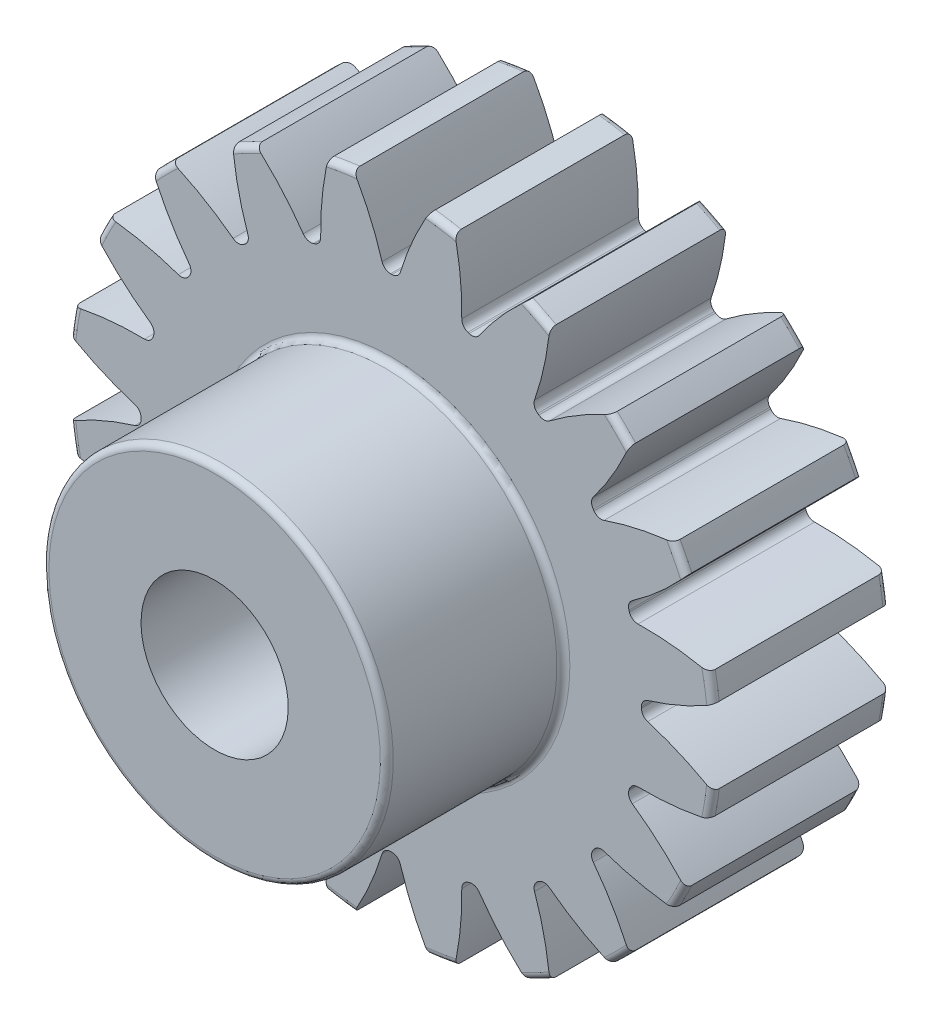
SolidWorks part; units mm, degrees
ref_plane "Front Plane" through (0, 0, 0) normal (0, 0, 1) x (1, 0, 0)
ref_plane "Top Plane" through (0, 0, 0) normal (0, 1, 0) x (1, 0, 0)
ref_plane "Right Plane" through (0, 0, 0) normal (1, 0, 0) x (0, 0, -1)
sketch "Sketch1" plane through (0, 0, 0) normal (0, 0, 1) x (1, 0, 0)
  line L0 (-254, 0) -> (254, 0) construction
  circle A0 centre (0, 0) radius 11 construction
  circle A1 centre (0, 0) radius 10 construction
  circle A2 centre (0, 0) radius 8.5 construction
  circle A3 centre (0, 0) radius 5.85 construction
  circle A4 centre (0, 0) radius 2.5 construction
  dimension "D2" = 1
  dimension "D3" = 2.5
  dimension "D1" = 2.5
sketch "Sketch2" plane through (0, 0, 0) normal (1, 0, 0) x (0, 0, -1)
  line L0 (0, 0) -> (-6, 0) construction
  line L1 (-6, 0) -> (-12, 0) construction
  dimension "Overall Width" = 12
  dimension "Face Width" = 6
sketch "Sketch4" plane through (0, 0, 0) normal (1, 0, 0) x (0, 0, -1)
  line L0 (-12, 2.5) -> (-12, 5.85)
  line L1 (-12, 5.85) -> (-6, 5.85)
  line L2 (-6, 5.85) -> (-6, 11)
  line L3 (-6, 11) -> (0, 11)
  line L4 (0, 11) -> (0, 2.5)
  line L5 (-6, 5.85) -> (-6, 0) construction
  line L6 (0, 11) -> (0, -11) construction
  line L7 (-6, 5.85) -> (0, 5.85) construction
  line L12 (-12, 2.5) -> (0, 2.5)
revolve "Revolve1" add sketch "Sketch4" angle 360 about L1
fillet "Fillet2" radius 0.22 4 edges at (0, 5.85, 12) (0, 5.85, 6) (0, 11, 6) (0, 11, 0)
sketch "Sketch7" plane through (0, 0, 6) normal (0, 0, 1) x (1, 0, 0)
  line L0 (0, 0) -> (0, 11) construction
  line L1 (0.7846, 9.9692) -> (1.2233, 10.9318) construction
  line L3 (1.7208, 10.8646) -> (1.5643, 9.8769) construction
  line L4 (1.5643, 9.8769) -> (1.3297, 8.3954) construction
  line L5 (0, 0) -> (1.3297, 8.3954) construction
  line L6 (0.7846, 9.9692) -> (0, 0) construction
  line L7 (0.7846, 9.9692) -> (0.863, 10.9661) construction
  line L8 (0.7846, 9.9692) -> (0, 0) construction
  circle A0 centre (0, 0) radius 11 construction
  arc A1 (-0.0232, 8.5) -> (0.0232, 8.5) centre (0, 0) cw
  circle A2 centre (0, 0) radius 8.5 construction
  arc A3 (-0.7846, 9.9692) -> (0.7846, 9.9692) centre (0, 0) cw construction
  circle A4 centre (0, 0) radius 10 construction
  arc A5 (2.1548, 10.7869) -> (1.284, 10.9248) centre (0, 0) ccw construction
  arc A6 (0.7846, 9.9692) -> (2.3345, 9.7237) centre (0, 0) cw construction
  arc A7 (-1.284, 10.9248) -> (1.284, 10.9248) centre (0, 0) cw
  arc A8 (0.3112, 8.7133) -> (1.284, 10.9248) centre (9.8842, 5.8222) cw
  arc A9 (-0.3112, 8.7133) -> (-1.284, 10.9248) centre (-9.8842, 5.8222) ccw
  arc A10 (-0.0232, 8.5) -> (-0.3112, 8.7133) centre (-0.024, 8.8) cw
  arc A11 (0.0232, 8.5) -> (0.3112, 8.7133) centre (0.024, 8.8) ccw
  point P26 (-0.2484, 8.4964)
  point P29 (0.2484, 8.4964)
  dimension "D4" = 0.3
  dimension "D5" = 10
  dimension "D3" = 20
  dimension "D1" = 3.1416
  dimension "D2" = 1.5708
extrude "Cut-Extrude2" cut sketch "Sketch7" against normal through all
pattern_circular "CirPattern1" count 20 over 360 about axis through (0, 0, 0) along (0, 0, 1) of "Cut-Extrude2"
equation "\"D1@Sketch1\"=2.5*(\"Pitch Dia.@Sketch1\"/\"Number of Teeth@Sketch1\")"
equation "\"D1@CirPattern1\"=\"Number of Teeth@Sketch1\""
equation "\"D1@Fillet2\"=\"OD@Sketch1\"*.01"
equation "\"D1@Sketch7\"=3.14159*(\"Pitch Dia.@Sketch1\"/\"Number of Teeth@Sketch1\")"
equation "\"D2@Sketch7\"=\"D1@Sketch7\"/2"
equation "\"D4@Sketch7\"=\"D1@Sketch7\"*.0955"
equation "\"D5@Sketch7\"=\"Pitch Dia.@Sketch1\"/2"
